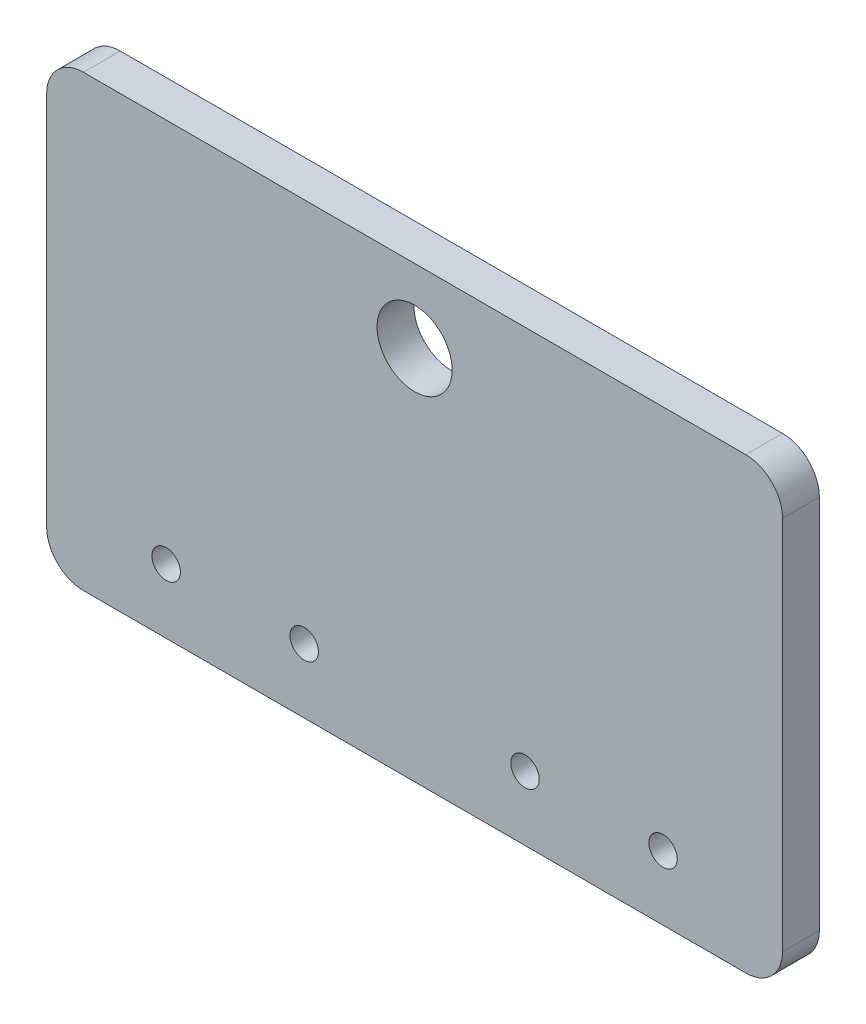
SolidWorks part; units mm, degrees
material "Acrylic (Medium-high impact)"
ref_plane "Front Plane" through (0, 0, 0) normal (0, 0, 1) x (1, 0, 0)
ref_plane "Top Plane" through (0, 0, 0) normal (0, 1, 0) x (1, 0, 0)
ref_plane "Right Plane" through (0, 0, 0) normal (1, 0, 0) x (0, 0, -1)
sketch "Sketch1" plane through (0, 0, 0) normal (0, 0, 1) x (1, 0, 0)
  line L1 (127, 77.47) -> (0, 77.47)
  line L2 (127, 77.47) -> (127, 0)
  line L3 (127, 0) -> (0, 0)
  line L4 (0, 77.47) -> (0, 0)
  line L5 (127, 77.47) -> (0, 0) construction
  line L6 (127, 0) -> (0, 77.47) construction
  point P0 (63.5, 38.735)
  dimension "D1" = 77.47
  dimension "D2" = 127
extrude "Boss-Extrude1" add sketch "Sketch1" along normal blind 6.35
hole_wizard "#8 Clearance Hole1" positions "Sketch6" profile "Sketch7" hole size "#8" standard "ANSI Inch" end condition through all
sketch "Sketch6" plane through (0, 0, 6.35) normal (0, 0, 1) x (1, 0, 0)
  line L2 (0, 0) -> (127, 0) construction
  line L3 (44.45, 11.1125) -> (82.55, 11.1125) construction
  line L5 (63.5, 0) -> (63.5, 11.1125) construction
  point P0 (20.6248, 11.1125)
  point P11 (44.45, 11.1125)
  point P13 (82.55, 11.1125)
  point P15 (106.3752, 11.1125)
  dimension "D1" = 23.8252
  dimension "D2" = 11.1125
  dimension "D4" = 23.8252
  dimension "D5" = 38.1
sketch "Sketch7" plane through (20.6248, 11.1125, 6.35) normal (1, 0, 0) x (0, -1, 0)
  line L0 (0, 0) -> (0, 6.35)
  line L1 (0, 6.35) -> (2.4574, 6.35)
  line L2 (2.4574, 6.35) -> (2.4574, 0)
  line L5 (2.4574, 0) -> (0, 0)
  line L11 (0, -6.35) -> (0, 107.95) construction
  dimension "Thru Hole Dia." = 4.9149
  dimension "Thru Hole Depth" = 6.35
fillet "Fillet1" radius 6.35 4 edges at (127, 0, 3.175) (127, 77.47, 3.175) (0, 77.47, 3.175) (0, 0, 3.175)
sketch "Sketch8" plane through (0, 0, 6.35) normal (0, 0, 1) x (1, 0, 0)
  line L0 (6.35, 0) -> (120.65, 0) construction
  line L1 (120.65, 77.47) -> (6.35, 77.47) construction
  circle A0 centre (63.5, 64.77) radius 6.477
  point P6 (63.5, 0)
  dimension "D1" = 12.954
  dimension "D2" = 12.7
extrude "Cut-Extrude1" cut sketch "Sketch8" against normal through all
